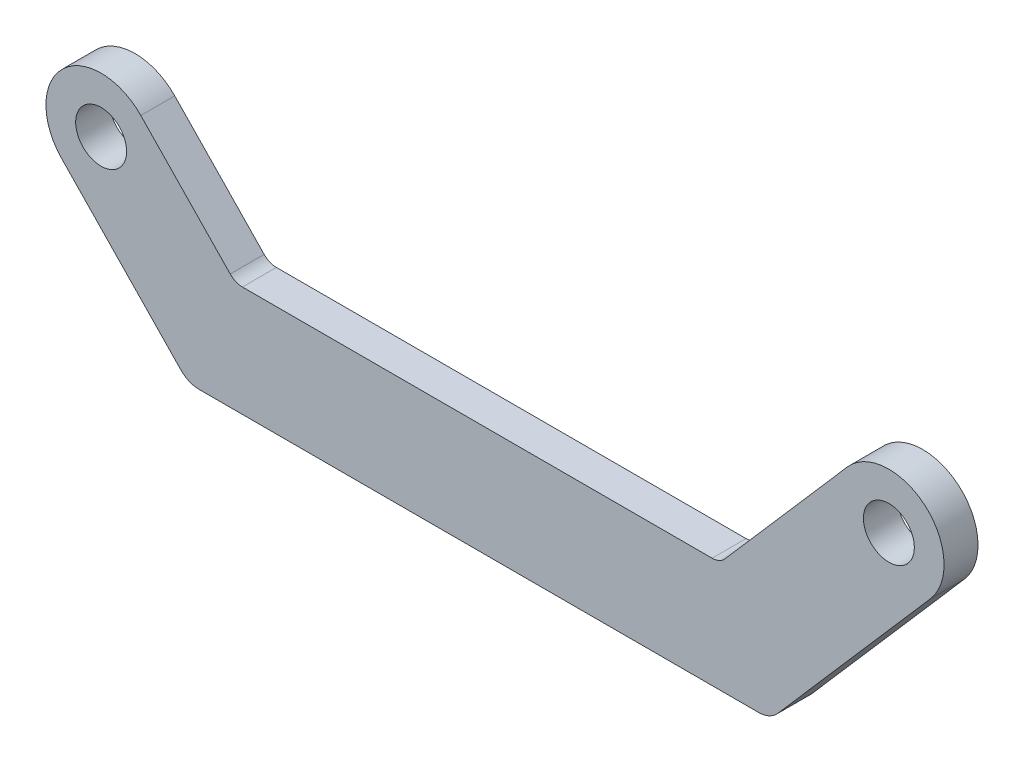
SolidWorks part; units mm, degrees
ref_plane "GAUCHE" through (0, 0, 0) normal (0, 0, 1) x (1, 0, 0)
ref_plane "Plan2" through (0, 0, 0) normal (0, 1, 0) x (1, 0, 0)
ref_plane "Plan3" through (0, 0, 0) normal (1, 0, 0) x (0, 0, -1)
sketch "Esquisse1" plane through (0, 0, 0) normal (0, 0, 1) x (1, 0, 0)
  line L0 (15.7959, -7) -> (72.8929, -7)
  line L1 (10.2777, -20) -> (78.8174, -20)
  line L3 (10.2777, -20) -> (-4.6757, -4.5153)
  line L4 (15.7959, -7) -> (4.6757, 4.5153)
  line L5 (72.8929, -7) -> (87.9006, 10.2644)
  line L6 (78.8174, -20) -> (97.7119, 1.7356)
  circle A0 centre (0, 0) radius 3
  circle A1 centre (92.8062, 6) radius 3
  arc A2 (97.7119, 1.7356) -> (87.9006, 10.2644) centre (92.8062, 6) ccw
  arc A3 (4.6757, 4.5153) -> (-4.6757, -4.5153) centre (0, 0) ccw
  dimension "D1" = 6
  dimension "D2" = 13
  dimension "D4" = 13
  dimension "D5" = 13
  dimension "D3" = 6
  dimension "D6" = 93
  dimension "D7" = 131
  dimension "D8" = 134
  dimension "D9" = 20
  dimension "D10" = 26
extrude "Base-Extrusion" add sketch "Esquisse1" along normal blind 4
fillet "Congé1" radius 3
fillet "Congé2" radius 2
